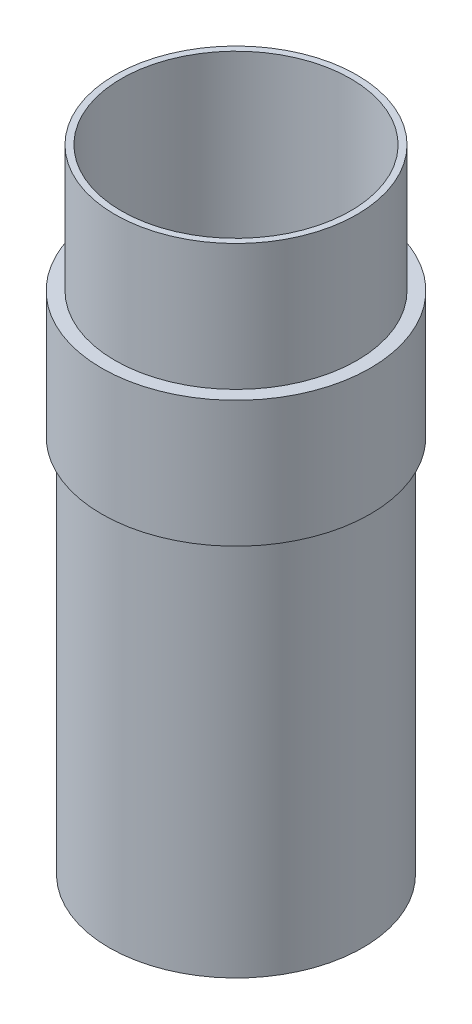
SolidWorks part; units mm, degrees
material "6061 Alloy"
ref_plane "Front Plane" through (0, 0, 0) normal (0, 0, 1) x (1, 0, 0)
ref_plane "Top Plane" through (0, 0, 0) normal (0, 1, 0) x (1, 0, 0)
ref_plane "Right Plane" through (0, 0, 0) normal (1, 0, 0) x (0, 0, -1)
sketch "Sketch1" plane through (0, 0, 0) normal (0, 0, 1) x (1, 0, 0)
  line L0 (0, 0) -> (0, 29.1323) construction
  line L1 (23.0403, -48.0385) -> (23.0403, 78.9615) construction
  line L2 (23.0403, 53.5615) -> (26.9875, 53.5615)
  line L4 (23.0403, 53.5615) -> (26.9875, 53.5615)
  line L7 (23.0403, 53.5615) -> (25.5143, 53.5615)
  line L8 (23.0403, 53.5615) -> (23.0403, -48.0385)
  line L9 (23.0403, -48.0385) -> (25.5143, -48.0385)
  line L10 (25.5143, 53.5615) -> (25.5143, -48.0385)
  line L11 (23.0403, 78.9615) -> (24.3103, 78.9615)
  line L12 (23.0403, 78.9615) -> (23.0403, 53.5615)
  line L13 (23.0403, 53.5615) -> (24.3103, 53.5615)
  line L14 (24.3103, 78.9615) -> (24.3103, 53.5615)
  line L15 (23.0403, 53.5615) -> (26.9875, 53.5615)
  line L16 (23.0403, 53.5615) -> (23.0403, 28.1615)
  line L17 (23.0403, 28.1615) -> (26.9875, 28.1615)
  line L18 (26.9875, 53.5615) -> (26.9875, 28.1615)
revolve "Revolve1" add sketch "Sketch1" angle 360 about L0
